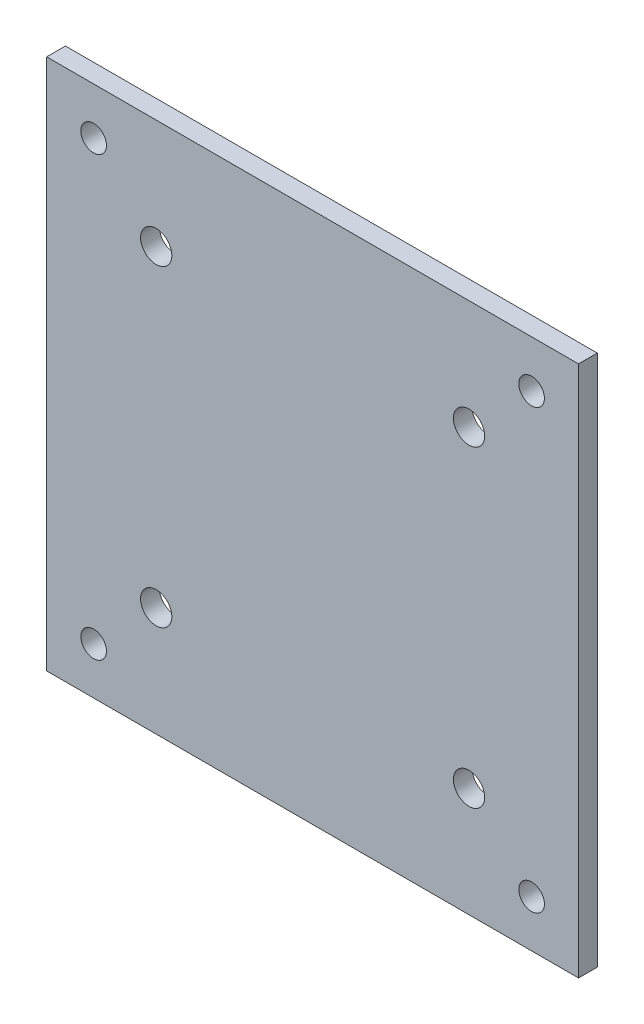
SolidWorks part; units mm, degrees
ref_plane "Front Plane" through (0, 0, 0) normal (0, 0, 1) x (1, 0, 0)
ref_plane "Top Plane" through (0, 0, 0) normal (0, 1, 0) x (1, 0, 0)
ref_plane "Right Plane" through (0, 0, 0) normal (1, 0, 0) x (0, 0, -1)
sketch "Sketch1" plane through (0, 0, 0) normal (0, 0, 1) x (1, 0, 0)
  line L1 (-32.5, 32.5) -> (32.5, 32.5)
  line L2 (-32.5, 32.5) -> (-32.5, -32.5)
  line L3 (-32.5, -32.5) -> (32.5, -32.5)
  line L4 (32.5, 32.5) -> (32.5, -32.5)
  line L5 (-32.5, 32.5) -> (32.5, -32.5) construction
  line L6 (-32.5, -32.5) -> (32.5, 32.5) construction
  circle A0 centre (-25, 25) radius 2.55
  circle A1 centre (25, 25) radius 2.55
  circle A2 centre (-25, -25) radius 2.55
  circle A3 centre (25, -25) radius 2.55
  point P0 (0, 0)
  dimension "D1" = 5.1
  dimension "D2" = 50
  dimension "D3" = 65
  dimension "D4" = 7.5
  dimension "D5" = 7.5
  dimension "D6" = 7.5
  dimension "D7" = 7.5
  dimension "D8" = 50
extrude "Boss-Extrude1" add sketch "Sketch1" along normal blind 3
sketch "Sketch2" plane through (0, 0, 3) normal (0, 0, 1) x (1, 0, 0)
  line L0 (0, 0) -> (42.5, 0) construction
  line L1 (-42.5, 42.5) -> (42.5, 42.5)
  line L2 (-42.5, 42.5) -> (-42.5, -42.5)
  line L3 (-42.5, -42.5) -> (42.5, -42.5)
  line L4 (42.5, 42.5) -> (42.5, -42.5)
  line L5 (-42.5, 42.5) -> (42.5, -42.5) construction
  line L6 (-42.5, -42.5) -> (42.5, 42.5) construction
  line L7 (0, 0) -> (0, 42.5) construction
  circle A0 centre (-35, 35) radius 2.05
  circle A1 centre (35, 35) radius 2.05
  circle A2 centre (35, -35) radius 2.05
  circle A3 centre (-35, -35) radius 2.05
  circle A4 centre (-25, 25) radius 2.5
  circle A5 centre (25, 25) radius 2.5
  circle A6 centre (25, -25) radius 2.5
  circle A7 centre (-25, -25) radius 2.5
  circle A8 centre (-25, 25) radius 2.55 construction
  point P0 (0, 0)
  dimension "D4" = 4.1
  dimension "D1" = 85
  dimension "D2" = 7.5
  dimension "D3" = 7.5
extrude "Boss-Extrude2" add sketch "Sketch2" against normal blind 3
